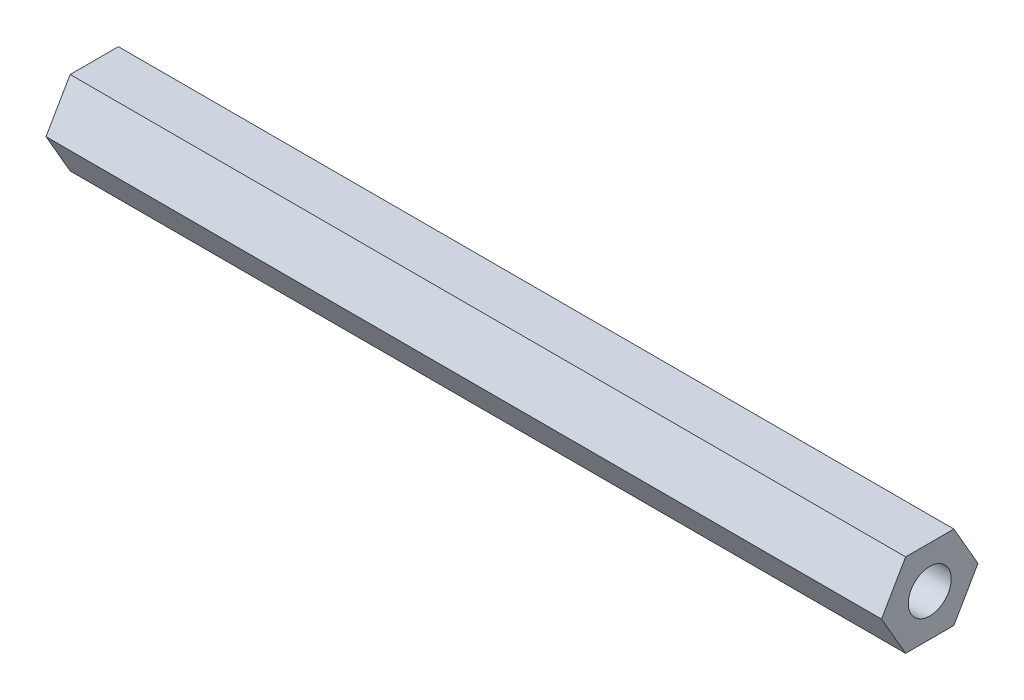
SolidWorks part; units mm, degrees
ref_plane "Front Plane" through (0, 0, 0) normal (0, 0, 1) x (1, 0, 0)
ref_plane "Top Plane" through (0, 0, 0) normal (0, 1, 0) x (1, 0, 0)
ref_plane "Right Plane" through (0, 0, 0) normal (1, 0, 0) x (0, 0, -1)
sketch "Sketch1" plane through (0, 0, 0) normal (1, 0, 0) x (0, 0, -1)
  line L1 (-3.6662, 6.35) -> (-7.3323, 0)
  line L2 (-7.3323, 0) -> (-3.6662, -6.35)
  line L3 (-3.6662, -6.35) -> (3.6662, -6.35)
  line L4 (3.6662, -6.35) -> (7.3323, 0)
  line L5 (7.3323, 0) -> (3.6662, 6.35)
  line L6 (3.6662, 6.35) -> (-3.6662, 6.35)
  circle A0 centre (0, 0) radius 6.35 construction
  dimension "D1" = 12.7
extrude "Boss-Extrude1" add sketch "Sketch1" along normal blind 127
sketch "Sketch2" plane through (127, 0, 0) normal (1, 0, 0) x (0, 0, -1)
  circle A0 centre (0, 0) radius 3.2639
  dimension "D1" = 6.5278
extrude "Cut-Extrude1" cut sketch "Sketch2" against normal blind 6.35
